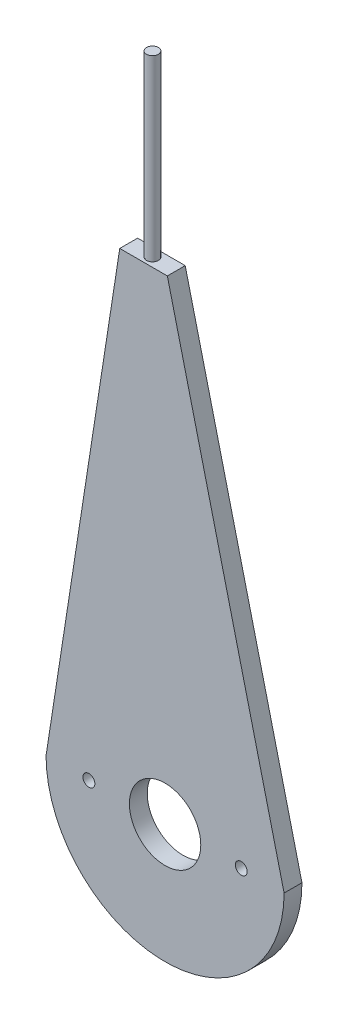
SolidWorks part; units mm, degrees
ref_plane "Front Plane" through (0, 0, 0) normal (0, 0, 1) x (1, 0, 0)
ref_plane "Top Plane" through (0, 0, 0) normal (0, 1, 0) x (1, 0, 0)
ref_plane "Right Plane" through (0, 0, 0) normal (1, 0, 0) x (0, 0, -1)
sketch "Sketch1" plane through (0, 0, 0) normal (0, 0, 1) x (1, 0, 0)
  line L0 (-34.2369, -273.4777) -> (-14.2369, -273.4777)
  line L1 (-14.2369, -273.4777) -> (34.8079, -473.4777)
  line L2 (-34.2369, -273.4777) -> (-65.1921, -473.4777)
  arc A1 (-65.1921, -473.4777) -> (34.8079, -473.4777) centre (-15.1921, -473.4777) ccw
  point P6 (-15.1921, -523.4777)
  dimension "D1" = 200
  dimension "D2" = 200
  dimension "D3" = 20
  dimension "D4" = 50
extrude "Boss-Extrude1" add sketch "Sketch1" along normal blind 7.5
sketch "Sketch3" plane through (0, -273.4777, 0) normal (0, 1, 0) x (1, 0, 0)
  line L0 (-14.2369, -7.5) -> (-14.2369, 0) construction
  line L1 (-14.2369, 0) -> (-34.2369, 0) construction
  circle A0 centre (-24.2369, -3.75) radius 2.5
  dimension "D1" = 10
  dimension "D2" = 3.75
extrude "Boss-Extrude2" add sketch "Sketch3" along normal blind 75
sketch "Sketch4" plane through (0, 0, 7.5) normal (0, 0, 1) x (1, 0, 0)
  circle A0 centre (-15.1921, -473.4777) radius 15
  circle A1 centre (16.8079, -473.4777) radius 2.5
  circle A2 centre (-47.1921, -473.4777) radius 2.5
  dimension "D1" = 30
  dimension "D2" = 5
  dimension "D3" = 5
  dimension "D4" = 32
  dimension "D5" = 32
extrude "Cut-Extrude1" cut sketch "Sketch4" against normal through all contours A0 | A2 | A1
